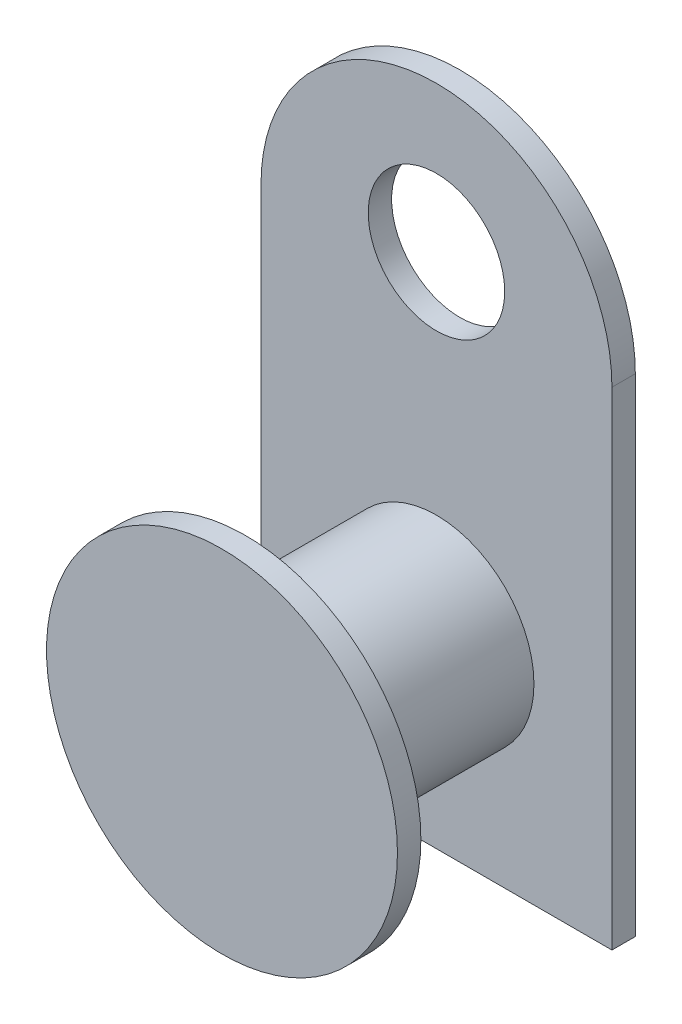
SolidWorks part; units mm, degrees
ref_plane "Plan de face" through (0, 0, 0) normal (0, 0, 1) x (1, 0, 0)
ref_plane "Plan de dessus" through (0, 0, 0) normal (0, 1, 0) x (1, 0, 0)
ref_plane "Plan de droite" through (0, 0, 0) normal (1, 0, 0) x (0, 0, -1)
sketch "Esquisse2" plane through (0, 0, 0) normal (0, 0, 1) x (1, 0, 0)
  line L0 (0, 170) -> (0, 150) construction
  line L1 (-45, 0) -> (45, 0)
  line L2 (45, 0) -> (45, 125)
  line L3 (-45, 125) -> (-45, 0)
  arc A0 (45, 125) -> (-45, 125) centre (0, 125) ccw
  circle A1 centre (0, 132.5) radius 17.5
  dimension "D3" = 35
  dimension "D1" = 90
  dimension "D2" = 125
  dimension "D4" = 20
extrude "Boss.-Extru.1" add sketch "Esquisse2" along normal blind 6
sketch "Esquisse3" plane through (0, 0, 6) normal (0, 0, 1) x (1, 0, 0)
  circle A0 centre (0, 49.0989) radius 25
  circle A1 centre (0, 49.0989) radius 22
  dimension "D1" = 50
  dimension "D2" = 3
extrude "Enlèv. mat.-Extru.1" cut sketch "Esquisse3" against normal blind 3
sketch "Esquisse4" plane through (0, 0, 3) normal (0, 0, 1) x (1, 0, 0)
  circle A0 centre (0, 49.0989) radius 22 construction
  circle A1 centre (0, 49.0989) radius 25
  circle A2 centre (0, 49.0989) radius 25
  circle A3 centre (0, 49.0989) radius 22
  dimension "D1" = 0
extrude "Boss.-Extru.2" add sketch "Esquisse4" along normal blind 55 separate body
sketch "Esquisse5" plane through (0, 0, 58) normal (0, 0, 1) x (1, 0, 0)
  circle A0 centre (0, 49.0989) radius 45
extrude "Boss.-Extru.3" add sketch "Esquisse5" along normal blind 6 from offset 3 separate body offset against normal yes
